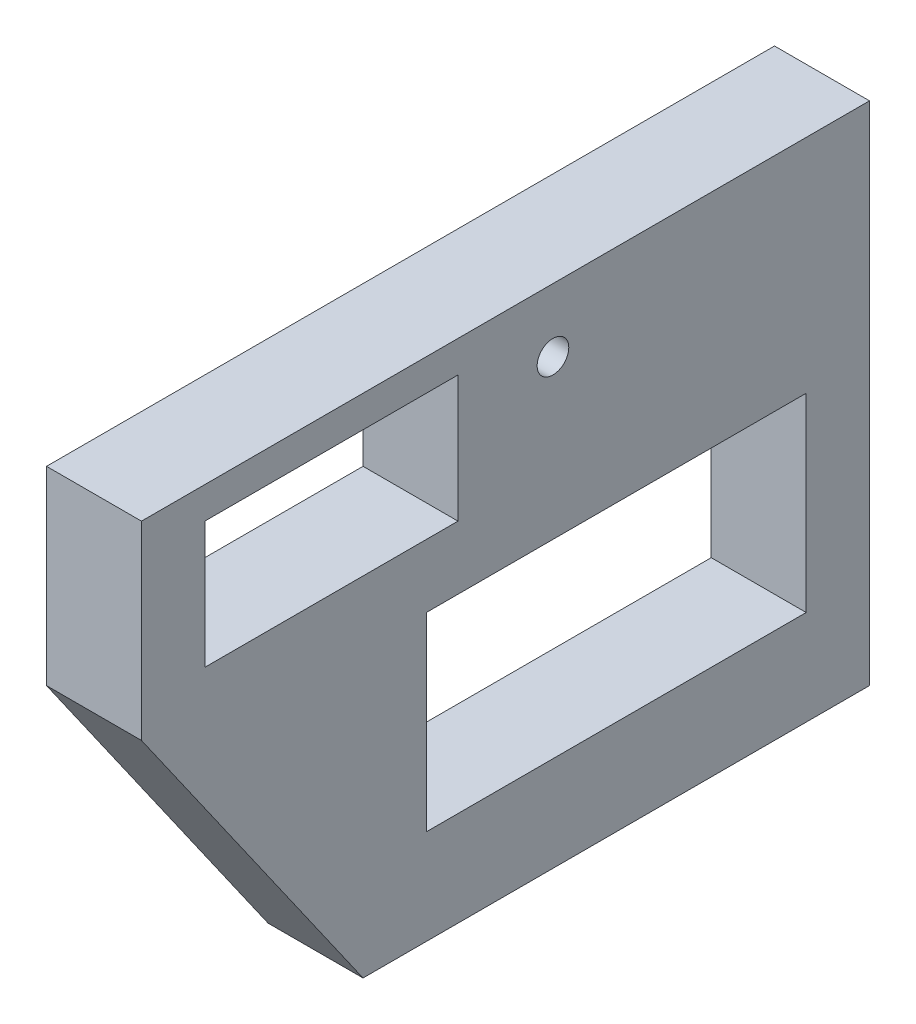
SolidWorks part; units mm, degrees
ref_plane "Front Plane" through (0, 0, 0) normal (0, 0, 1) x (1, 0, 0)
ref_plane "Top Plane" through (0, 0, 0) normal (0, 1, 0) x (1, 0, 0)
ref_plane "Right Plane" through (0, 0, 0) normal (1, 0, 0) x (0, 0, -1)
sketch "Sketch1" plane through (0, 0, 0) normal (1, 0, 0) x (0, 0, -1)
  line L0 (-115, 50) -> (-80, 0)
  line L1 (0, 80) -> (-115, 80)
  line L2 (0, 80) -> (0, 0)
  line L3 (0, 0) -> (-80, 0)
  line L4 (-115, 80) -> (-115, 50)
  line L6 (-105, 75) -> (-65, 75)
  line L7 (-105, 75) -> (-105, 55)
  line L8 (-105, 55) -> (-65, 55)
  line L9 (-65, 75) -> (-65, 55)
  line L10 (-70, 45) -> (-10, 45)
  line L11 (-70, 45) -> (-70, 15)
  line L12 (-70, 15) -> (-10, 15)
  line L13 (-10, 45) -> (-10, 15)
  dimension "D1" = 115
  dimension "D2" = 80
  dimension "D3" = 30
  dimension "D4" = 80
  dimension "D5" = 40
  dimension "D6" = 20
  dimension "D7" = 5
  dimension "D8" = 10
  dimension "D9" = 60
  dimension "D10" = 30
  dimension "D11" = 15
  dimension "D12" = 10
extrude "Boss-Extrude1" add sketch "Sketch1" along normal blind 15
sketch "Sketch2" plane through (15, 0, 0) normal (1, 0, 0) x (0, 0, -1)
  line L0 (0, 80) -> (-115, 80) construction
  line L1 (-115, 80) -> (-115, 50) construction
  circle A0 centre (-50, 70) radius 2.5
  point P0 (-50, 70)
  dimension "D3" = 5
  dimension "D1" = 10
  dimension "D2" = 65
extrude "Cut-Extrude1" cut sketch "Sketch2" against normal blind 15
